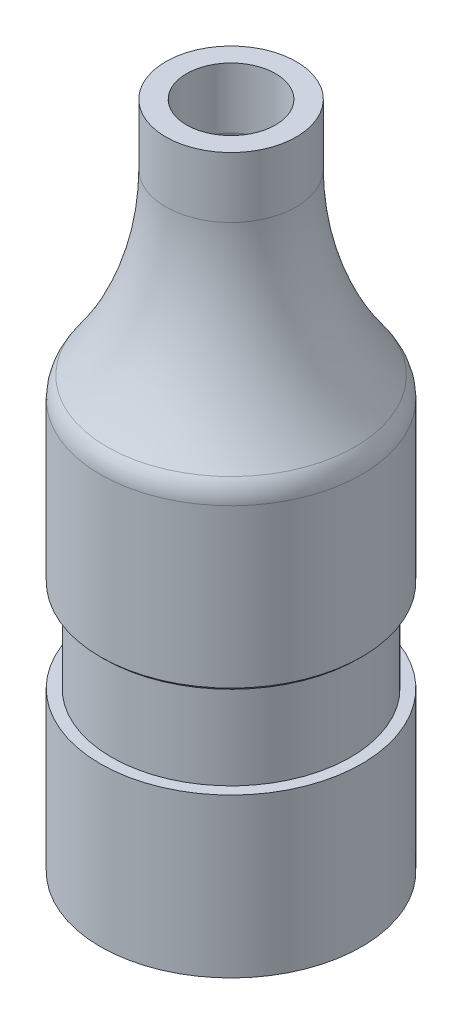
SolidWorks part; units mm, degrees
ref_plane "Front Plane" through (0, 0, 0) normal (0, 0, 1) x (1, 0, 0)
ref_plane "Top Plane" through (0, 0, 0) normal (0, 1, 0) x (1, 0, 0)
ref_plane "Right Plane" through (0, 0, 0) normal (1, 0, 0) x (0, 0, -1)
sketch "Sketch3" plane through (0, 0, 0) normal (0, 0, 1) x (1, 0, 0)
  line L0 (0, 43.62) -> (0, 0) construction
  line L1 (6.35, 5) -> (7.55, 5)
  line L2 (7.55, 5) -> (7.55, 14.15)
  line L3 (7.55, 14.15) -> (6.9, 14.15)
  line L4 (6.9, 14.15) -> (6.9, 19.3)
  line L5 (6.9, 19.3) -> (7.35, 19.3)
  line L6 (7.55, 19.5) -> (7.55, 28.6225)
  line L9 (4.95, 20.5) -> (4.75, 20.5)
  line L10 (4.75, 20.5) -> (4.75, 20.4964)
  line L11 (6.35, 5) -> (6.35, 12.95)
  line L12 (6.35, 12.95) -> (4.95, 12.95)
  line L13 (4.95, 12.95) -> (4.95, 20.5)
  line L14 (0, 0) -> (27.0488, 0) construction
  line L15 (4.75, 20.4964) -> (4.75, 29.3)
  line L16 (3.77, 43.62) -> (2.57, 43.62)
  line L17 (3.77, 43.62) -> (3.77, 40.12)
  line L18 (2.57, 43.62) -> (2.57, 40.12)
  line L19 (7.35, 19.3) -> (7.55, 19.5)
  line L20 (2.57, 40.12) -> (4.75, 29.3)
  arc A0 (3.77, 40.12) -> (7.1598, 29.8093) centre (21.1458, 40.12) ccw
  arc A2 (7.55, 28.6225) -> (7.1598, 29.8093) centre (5.55, 28.6225) ccw
  point P3 (6.95, 5)
  point P5 (7.55, 19.3)
  point P19 (7.225, 14.15)
  point P24 (6.35, 8.975)
  point P27 (7.55, 29.3)
  dimension "D2" = 0.65
  dimension "D17" = 2
  dimension "D18" = 6.35
  dimension "D3" = 4.95
  dimension "D4" = 0.65
  dimension "D5" = 1.2
  dimension "D6" = 9.15
  dimension "D7" = 5.15
  dimension "D8" = 1.2
  dimension "D9" = 4.75
  dimension "D10" = 1.2
  dimension "D11" = 10
  dimension "D12" = 5
  dimension "D13" = 38.62
  dimension "D14" = 2.57
  dimension "D15" = 1.2
  dimension "D16" = 3.5
revolve "Revolve1" add sketch "Sketch3" angle 360 about L0
